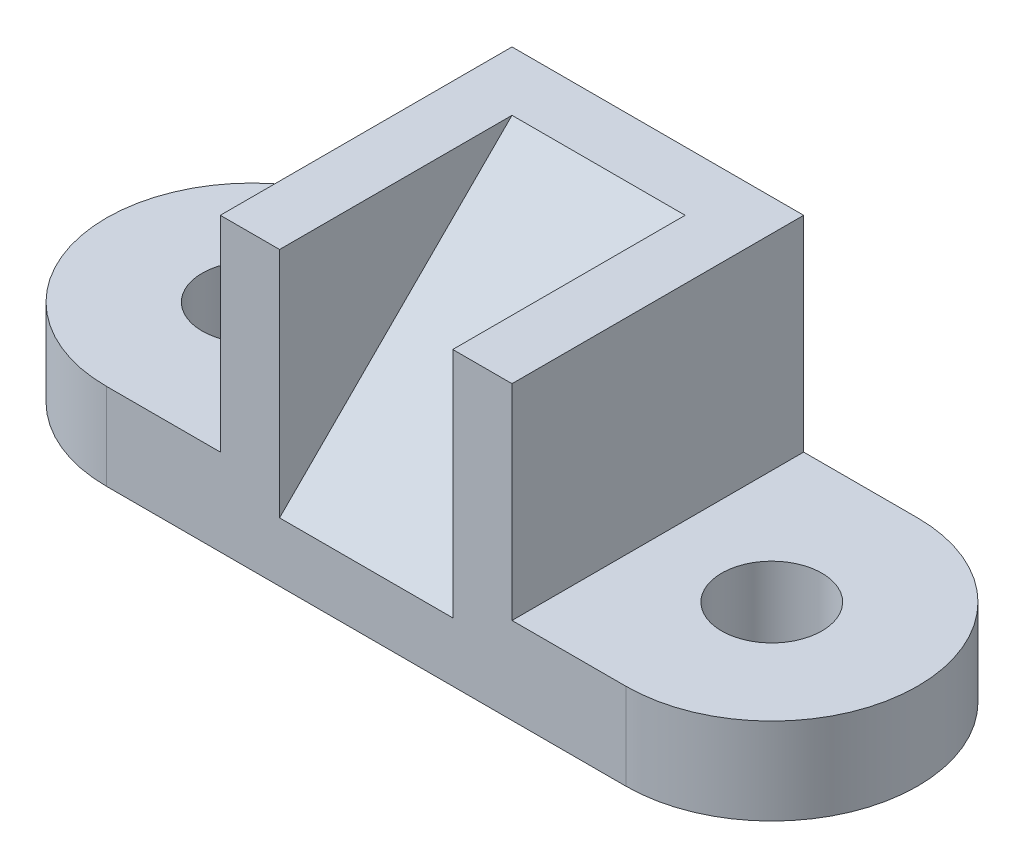
SolidWorks part; units mm, degrees
ref_plane "Front Plane" through (0, 0, 0) normal (0, 0, 1) x (1, 0, 0)
ref_plane "Top Plane" through (0, 0, 0) normal (0, 1, 0) x (1, 0, 0)
ref_plane "Right Plane" through (0, 0, 0) normal (1, 0, 0) x (0, 0, -1)
sketch "Sketch1" plane through (0, 0, 0) normal (0, 1, 0) x (1, 0, 0)
  line L1 (-57, 32) -> (57, 32)
  line L3 (-57, -32) -> (57, -32)
  line L5 (-57, 32) -> (57, -32) construction
  line L6 (-57, -32) -> (57, 32) construction
  arc A0 (-57, 32) -> (-57, -32) centre (-57, 0) ccw
  arc A1 (57, -32) -> (57, 32) centre (57, 0) ccw
  circle A2 centre (-57, 0) radius 11
  circle A3 centre (57, 0) radius 11
  point P0 (0, 0)
  dimension "D3" = 64
  dimension "D4" = 64
  dimension "D5" = 22
  dimension "D6" = 22
  dimension "D1" = 114
  dimension "D2" = 64
extrude "Boss-Extrude1" add sketch "Sketch1" along normal blind 19
sketch "Sketch2" plane through (0, 19, 0) normal (0, 1, 0) x (1, 0, 0)
  line L0 (-57, -32) -> (57, -32) construction
  line L1 (-32, 32) -> (32, 32)
  line L2 (-32, 32) -> (-32, -32)
  line L3 (-32, -32) -> (32, -32)
  line L4 (32, 32) -> (32, -32)
  line L5 (-32, 32) -> (32, -32) construction
  line L6 (-32, -32) -> (32, 32) construction
  point P0 (0, 0)
  dimension "D1" = 64
extrude "Boss-Extrude2" add sketch "Sketch2" along normal blind 45
ref_plane "Plane1" through (0, 0, 0) normal (1, 0, 0) x (0, 0, -1)
sketch "Sketch3" plane through (0, 0, 0) normal (1, 0, 0) x (0, 0, -1)
  line L0 (-32, 13) -> (-32, 64)
  line L1 (-32, 19) -> (-32, 0) construction
  line L2 (-32, 64) -> (19, 64)
  line L3 (-32, 64) -> (32, 64) construction
  line L4 (19, 64) -> (-32, 13)
  line L5 (-32, 0) -> (32, 0) construction
  line L6 (32, 64) -> (32, 19) construction
  dimension "D1" = 13
  dimension "D2" = 13
extrude "Cut-Extrude2" cut sketch "Sketch3" against normal mid plane 38
